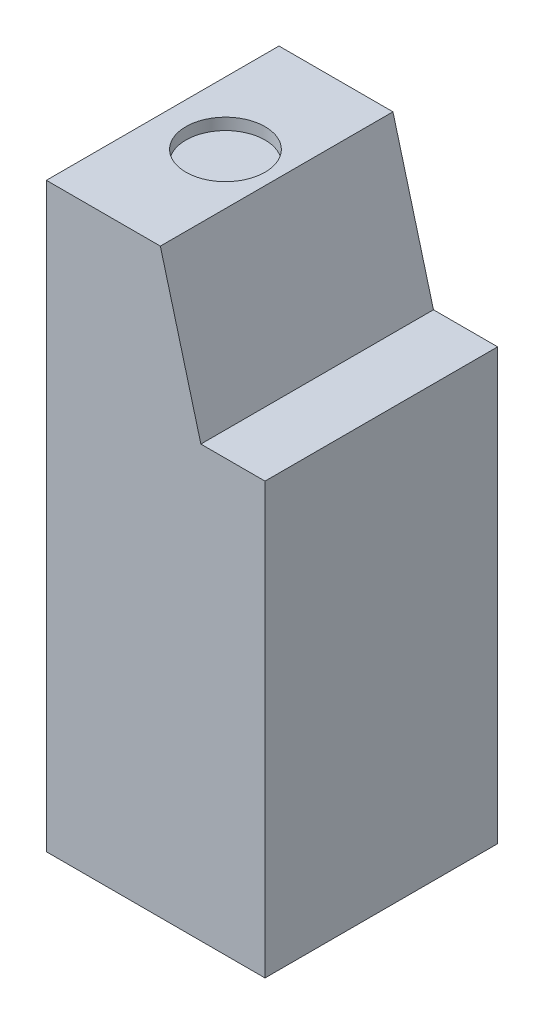
SolidWorks part; units mm, degrees
ref_plane "Front" through (0, 0, 0) normal (0, 0, 1) x (1, 0, 0)
ref_plane "Top" through (0, 0, 0) normal (0, 1, 0) x (1, 0, 0)
ref_plane "Right" through (0, 0, 0) normal (1, 0, 0) x (0, 0, -1)
sketch "Base Sketch" plane through (0, 0, 0) normal (0, 0, 1) x (1, 0, 0)
  line L1 (0, 0) -> (0, 18.5)
  line L2 (0, 18.5) -> (-9.4, 18.5)
  line L5 (-9.4, 18.5) -> (-9.4, 0)
  line L6 (-9.4, 0) -> (0, 0)
  dimension "D1" = 9.4
  dimension "D2" = 18.5
extrude "Base" add sketch "Base Sketch" along normal mid plane 10
sketch "Base Top Sketch" plane through (0, 0, 0) normal (0, 0, 1) x (1, 0, 0)
  line L0 (0, 18.5) -> (-9.4, 18.5) construction
  line L1 (-2.7583, 18.5) -> (-9.4, 18.5)
  line L2 (-9.4, 18.5) -> (-9.4, 25)
  line L3 (-9.4, 25) -> (-4.5, 25)
  line L4 (-4.5, 25) -> (-2.7583, 18.5)
  line L7 (0, 0) -> (0, 18.5) construction
  dimension "D1" = 4.5
  dimension "D2" = 6.5
  dimension "D3" = 105
extrude "Base Top" add sketch "Base Top Sketch" along normal mid plane 10
sketch "Man-op cutout sketch" plane through (0, 25, 0) normal (0, 1, 0) x (-1, 0, 0)
  line L2 (3.85, 0) -> (-3.85, 0) construction
  line L3 (9.4, 5) -> (9.4, -5) construction
  circle A0 centre (6.7, 0) radius 1.7
  dimension "D1" = 3.4
  dimension "D2" = 2.7
extrude "Man-op cutout" cut sketch "Man-op cutout sketch" against normal blind 0.5
